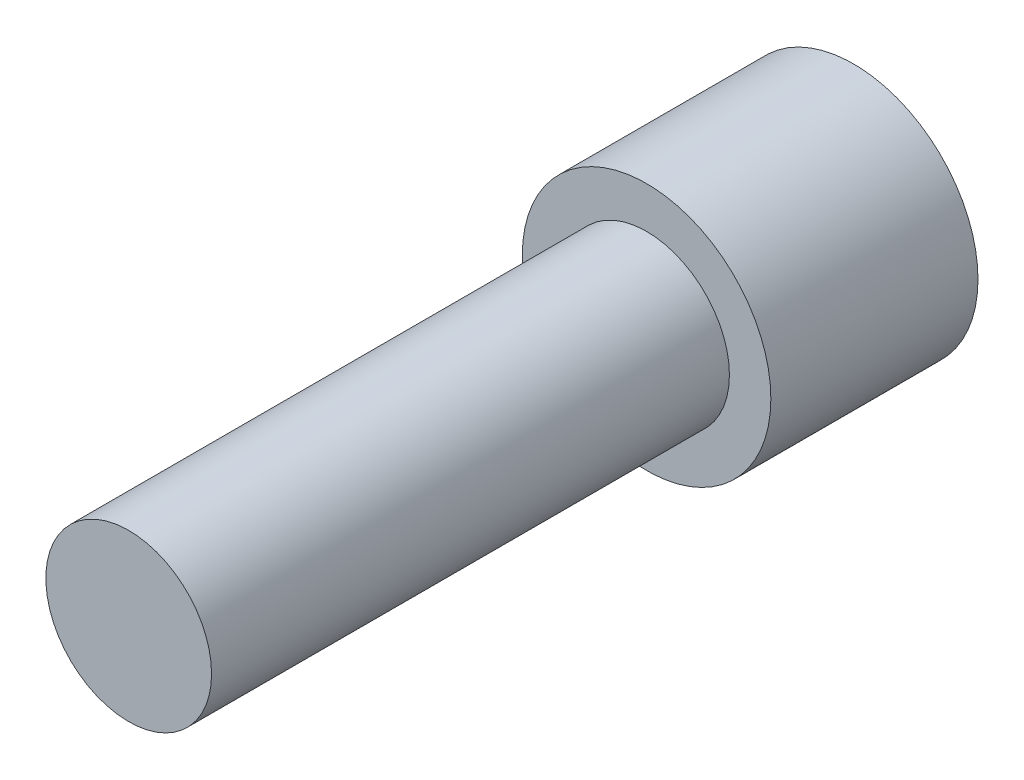
SolidWorks part; units mm, degrees
ref_plane "Front Plane" through (0, 0, 0) normal (0, 0, 1) x (1, 0, 0)
ref_plane "Top Plane" through (0, 0, 0) normal (0, 1, 0) x (1, 0, 0)
ref_plane "Right Plane" through (0, 0, 0) normal (1, 0, 0) x (0, 0, -1)
sketch "Sketch1" plane through (0, 0, 0) normal (0, 0, 1) x (1, 0, 0)
  circle A0 centre (0, 0) radius 6
  dimension "D1" = 12
extrude "Boss-Extrude1" add sketch "Sketch1" along normal blind 10
sketch "Sketch2" plane through (0, 0, 0) normal (0, 0, -1) x (-1, 0, 0)
  line L1 (2.3094, 4) -> (-2.3094, 4)
  line L2 (-2.3094, 4) -> (-4.6188, 0)
  line L3 (-4.6188, 0) -> (-2.3094, -4)
  line L4 (-2.3094, -4) -> (2.3094, -4)
  line L5 (2.3094, -4) -> (4.6188, 0)
  line L6 (4.6188, 0) -> (2.3094, 4)
  circle A0 centre (0, 0) radius 4 construction
  dimension "D1" = 8
sketch "Sketch3" plane through (0, 0, 10) normal (0, 0, 1) x (1, 0, 0)
  circle A0 centre (0, 0) radius 4
extrude "Boss-Extrude2" add sketch "Sketch3" along normal blind 25
extrude "Cut-Extrude1" cut sketch "Sketch2" against normal blind 7
